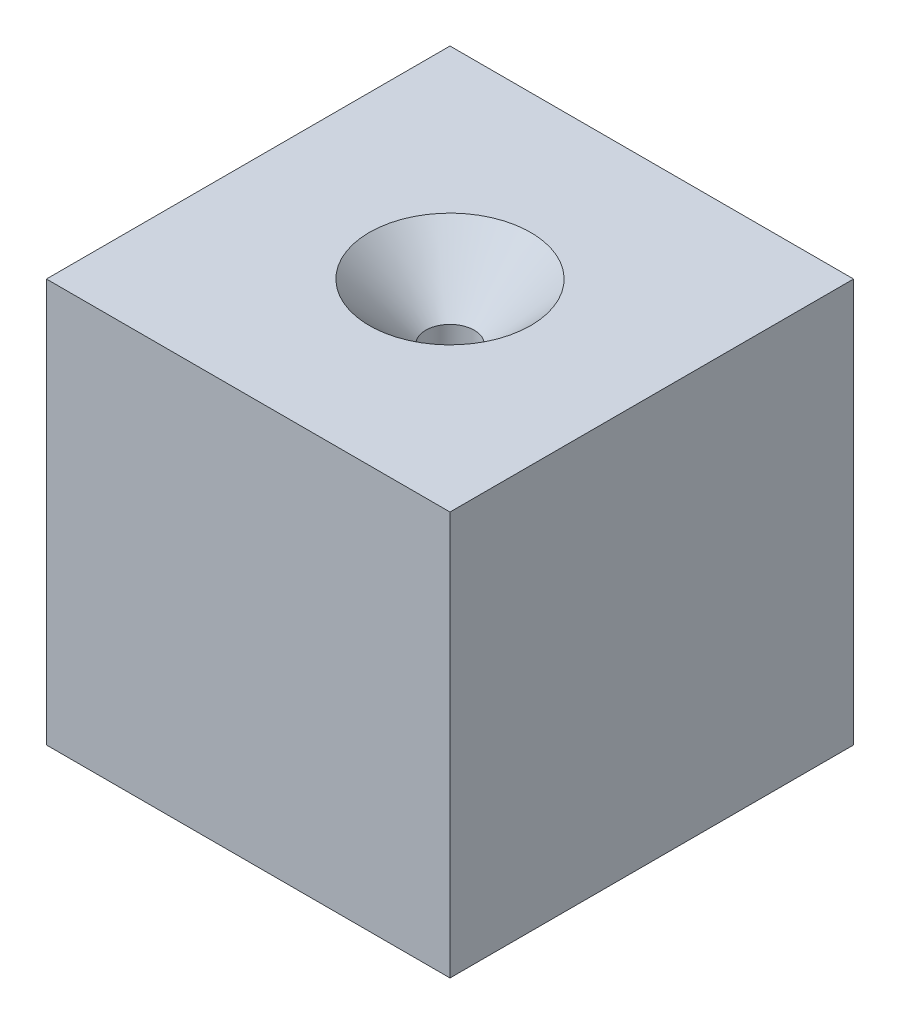
SolidWorks part; units mm, degrees
ref_plane "前视基准面" through (0, 0, 0) normal (0, 0, 1) x (1, 0, 0)
ref_plane "上视基准面" through (0, 0, 0) normal (0, 1, 0) x (1, 0, 0)
ref_plane "右视基准面" through (0, 0, 0) normal (1, 0, 0) x (0, 0, -1)
other "草"
sketch "草图1" plane through (0, 0, 0) normal (0, 0, 1) x (1, 0, 0)
  line L1 (-36.0964, 20.5882) -> (13.9036, 20.5882)
  line L2 (-36.0964, 20.5882) -> (-36.0964, -29.4118)
  line L3 (-36.0964, -29.4118) -> (13.9036, -29.4118)
  line L4 (13.9036, 20.5882) -> (13.9036, -29.4118)
  point P0 (0, 0)
  dimension "D1" = 50
  dimension "D2" = 50
extrude "凸台-拉伸1" add sketch "草图1" along normal blind 50
ref_plane "基准面1" through (-11.0964, 0, 0) normal (1, 0, 0) x (0, 0, -1)
sketch "草图3" plane through (-11.0964, 0, 0) normal (1, 0, 0) x (0, 0, -1)
  line L0 (-25, 20.5882) -> (-35, 20.5882)
  line L1 (-50, 20.5882) -> (0, 20.5882) construction
  line L2 (-35, 20.5882) -> (-28, 13.5983)
  line L3 (-25, 20.5882) -> (-25, -29.4118)
  line L4 (-28, 13.5983) -> (-28, -29.4118)
  line L5 (-50, -29.4118) -> (0, -29.4118) construction
  line L6 (-25, 20.5882) -> (-25, -29.4118) construction
  line L7 (-28, -29.4118) -> (-25, -29.4118)
  point P4 (-27.8437, 13.5983)
  point P5 (-28.5262, 18.7616)
  dimension "D1" = 10
  dimension "D2" = 3
  dimension "D3" = 134.959
revolve "切除-旋转1" cut sketch "草图3" angle 360 about L6
